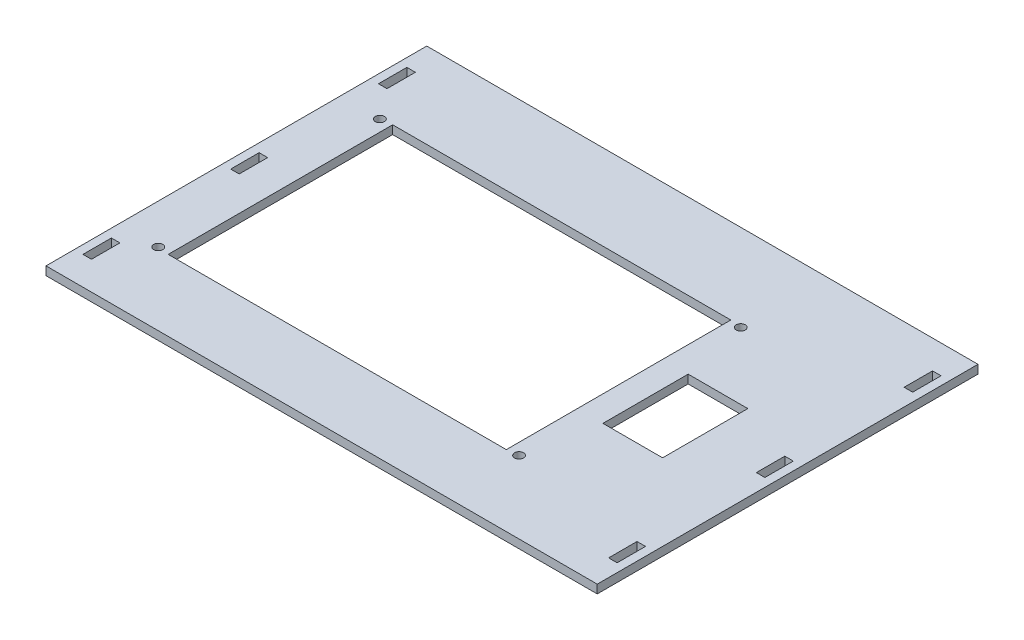
SolidWorks part; units mm, degrees
material "ABS"
ref_plane "Front Plane" through (0, 0, 0) normal (0, 0, 1) x (1, 0, 0)
ref_plane "Top Plane" through (0, 0, 0) normal (0, 1, 0) x (1, 0, 0)
ref_plane "Right Plane" through (0, 0, 0) normal (1, 0, 0) x (0, 0, -1)
sketch "Sketch1" plane through (0, 0, 0) normal (0, 1, 0) x (1, 0, 0)
  line L1 (0, 0) -> (194, 0)
  line L3 (0, 134) -> (194, 134)
  line L4 (194, 0) -> (194, 14.55)
  line L5 (18, 104) -> (137, 104)
  line L6 (18, 104) -> (18, 25)
  line L7 (18, 25) -> (137, 25)
  line L8 (137, 104) -> (137, 25)
  line L13 (146, 80) -> (167, 80)
  line L14 (146, 80) -> (146, 50)
  line L15 (146, 50) -> (167, 50)
  line L16 (167, 80) -> (167, 50)
  line L53 (0, 0) -> (0, 134)
  line L65 (194, 14.55) -> (194, 114.55)
  line L66 (194, 114.55) -> (194, 134)
  line L68 (3, 124) -> (6, 124)
  line L69 (3, 124) -> (3, 114)
  line L70 (3, 114) -> (6, 114)
  line L71 (6, 124) -> (6, 114)
  line L72 (3, 72) -> (6, 72)
  line L73 (3, 72) -> (3, 62)
  line L74 (3, 62) -> (6, 62)
  line L75 (6, 72) -> (6, 62)
  line L76 (3, 20) -> (6, 20)
  line L77 (3, 20) -> (3, 10)
  line L78 (3, 10) -> (6, 10)
  line L79 (6, 20) -> (6, 10)
  line L80 (188, 124) -> (191, 124)
  line L81 (188, 124) -> (188, 114)
  line L82 (188, 114) -> (191, 114)
  line L83 (191, 124) -> (191, 114)
  line L84 (188, 72) -> (191, 72)
  line L85 (188, 72) -> (188, 62)
  line L86 (188, 62) -> (191, 62)
  line L87 (191, 72) -> (191, 62)
  line L88 (188, 20) -> (191, 20)
  line L89 (188, 20) -> (188, 10)
  line L90 (188, 10) -> (191, 10)
  line L91 (191, 20) -> (191, 10)
  circle A0 centre (14, 103.5) radius 1.6
  circle A1 centre (141, 103.5) radius 1.6
  circle A2 centre (141, 25.5) radius 1.6
  circle A3 centre (14, 25.5) radius 1.6
  point P13 (156.5, 50)
  dimension "D11" = 3.2
  dimension "D12" = 78
  dimension "D1" = 194
  dimension "D2" = 134
  dimension "D3" = 119
  dimension "D4" = 79
  dimension "D5" = 3
  dimension "D6" = 25
  dimension "D7" = 21
  dimension "D8" = 30
  dimension "D9" = 25
  dimension "D10" = 27
  dimension "D13" = 127
  dimension "D14" = 4
  dimension "D15" = 0.5
  dimension "D16" = 3
  dimension "D17" = 3
  dimension "D18" = 3
  dimension "D19" = 3
  dimension "D20" = 3
  dimension "D21" = 10
  dimension "D22" = 10
  dimension "D23" = 10
  dimension "D24" = 10
  dimension "D25" = 10
  dimension "D26" = 10
  dimension "D27" = 10
  dimension "D28" = 10
  dimension "D29" = 42
  dimension "D30" = 3
  dimension "D31" = 3
  dimension "D32" = 3
  dimension "D33" = 3
  dimension "D34" = 3
  dimension "D35" = 3
  dimension "D36" = 10
  dimension "D37" = 10
  dimension "D38" = 42
  dimension "D39" = 42
  dimension "D40" = 18
extrude "Boss-Extrude1" add sketch "Sketch1" along normal blind 3
